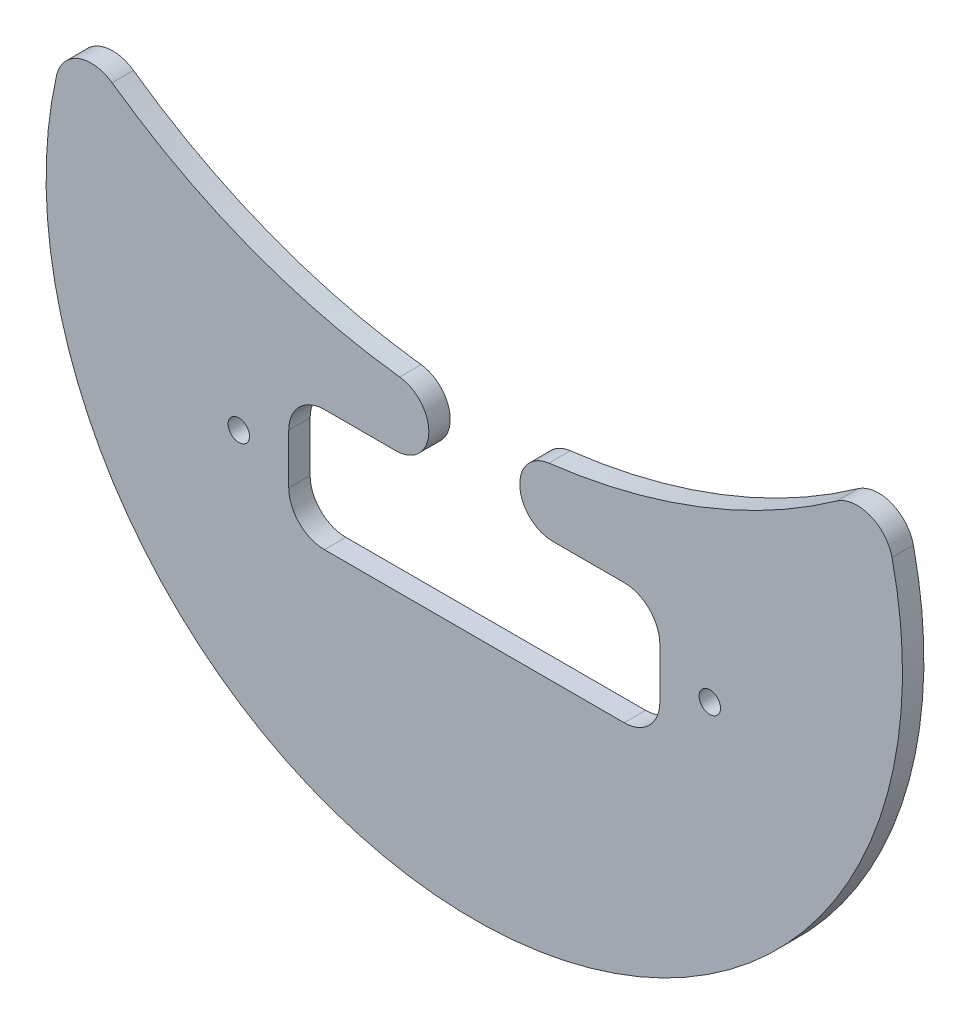
SolidWorks part; units mm, degrees
ref_plane "Front Plane" through (0, 0, 0) normal (0, 0, 1) x (1, 0, 0)
ref_plane "Top Plane" through (0, 0, 0) normal (0, 1, 0) x (1, 0, 0)
ref_plane "Right Plane" through (0, 0, 0) normal (1, 0, 0) x (0, 0, -1)
sketch "Sketch1" plane through (0, 0, 0) normal (0, 0, 1) x (1, 0, 0)
  line L0 (-23.2486, 31.85) -> (23.5514, 31.85) construction
  line L1 (0.1514, 32.35) -> (0.1514, 52.6395) construction
  line L2 (-25.8486, 6.75) -> (26.1514, 6.75)
  line L3 (-25.8486, 6.75) -> (-25.8486, 23.75)
  line L4 (-25.8486, 23.75) -> (-10.8486, 23.75)
  line L5 (26.1514, 6.75) -> (26.1514, 23.75)
  line L6 (11.1514, 23.75) -> (26.1514, 23.75)
  arc A0 (-56.2301, 52.8712) -> (56.533, 52.8712) centre (0.1514, 32.35) ccw
  arc A1 (-56.2301, 52.8712) -> (-10.2972, 32.9745) centre (0.1514, 120.0641) ccw
  arc A2 (-10.2972, 32.9745) -> (-10.8486, 23.75) centre (-10.8486, 28.3788) cw
  arc A3 (10.6, 32.9745) -> (11.1514, 23.75) centre (11.1514, 28.3788) ccw
  arc A4 (10.6, 32.9745) -> (56.533, 52.8712) centre (0.1514, 120.0641) ccw
  circle A5 centre (-32.8486, 15.25) radius 1.5
  circle A6 centre (33.1514, 15.25) radius 1.5
  point P3 (0.1514, 32.35)
  point P4 (0.1514, 31.85)
  point P8 (0.1514, -27.65)
  dimension "D1" = 0.5
  dimension "D2" = 60
  dimension "D3" = 140
  dimension "D5" = 3
  dimension "D4" = 15
extrude "Boss-Extrude1" add sketch "Sketch1" along normal blind 3
fillet "Fillet4" radius 5 6 edges at (-25.8486, 23.75, 1.5) (-25.8486, 6.75, 1.5) (26.1514, 6.75, 1.5) (26.1514, 23.75, 1.5) (-56.2301, 52.8712, 1.5) (56.533, 52.8712, 1.5)
